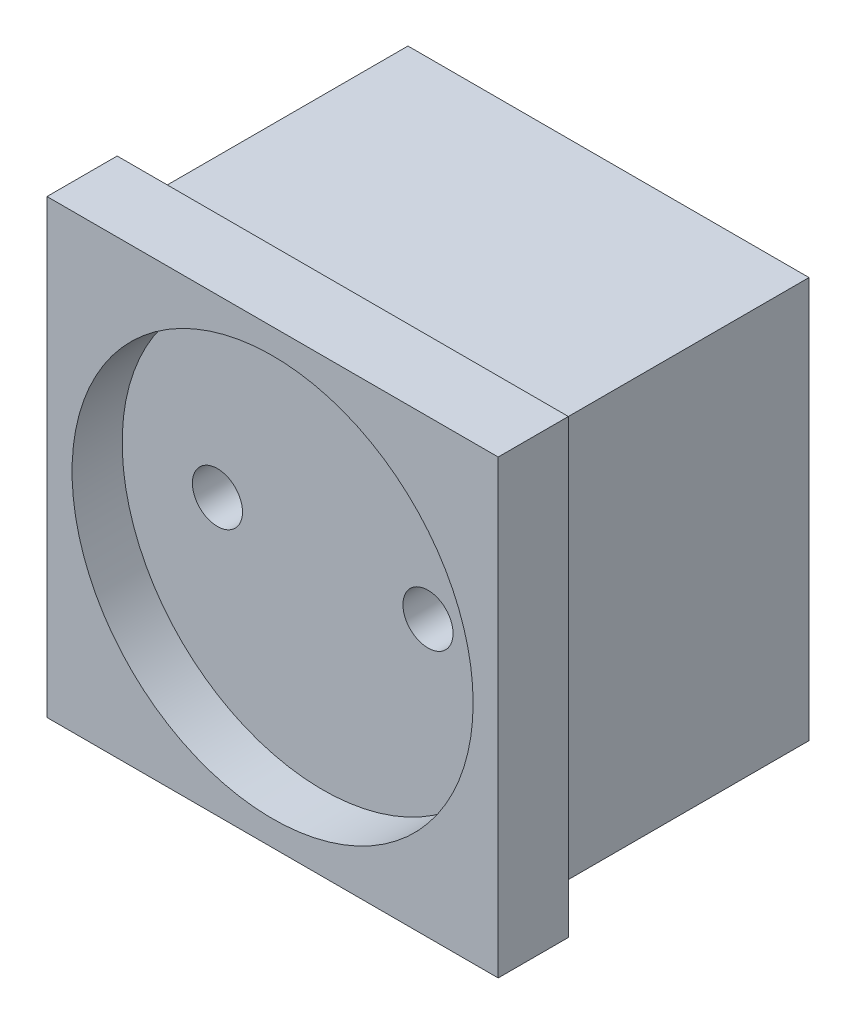
SolidWorks part; units mm, degrees
ref_plane "Спереди" through (0, 0, 0) normal (0, 0, 1) x (1, 0, 0)
ref_plane "Сверху" through (0, 0, 0) normal (0, 1, 0) x (1, 0, 0)
ref_plane "Справа" through (0, 0, 0) normal (1, 0, 0) x (0, 0, -1)
sketch "Эскиз1" plane through (0, 0, 0) normal (0, 0, 1) x (1, 0, 0)
  line L1 (-20, -20) -> (20, -20)
  line L2 (-20, -20) -> (-20, 20)
  line L3 (-20, 20) -> (20, 20)
  line L4 (20, -20) -> (20, 20)
  line L5 (-20, -20) -> (20, 20) construction
  line L6 (-20, 20) -> (20, -20) construction
  point P0 (0, 0)
  dimension "D1" = 40
extrude "Бобышка-Вытянуть1" add sketch "Эскиз1" along normal blind 33.5
sketch "Эскиз2" plane through (0, 0, 33.5) normal (0, 0, 1) x (1, 0, 0)
  line L1 (22.5, -22.5) -> (-22.5, -22.5)
  line L2 (22.5, -22.5) -> (22.5, 22.5)
  line L3 (22.5, 22.5) -> (-22.5, 22.5)
  line L4 (-22.5, -22.5) -> (-22.5, 22.5)
  line L5 (22.5, -22.5) -> (-22.5, 22.5) construction
  line L6 (22.5, 22.5) -> (-22.5, -22.5) construction
  point P0 (0, 0)
  dimension "D1" = 45
extrude "Бобышка-Вытянуть2" add sketch "Эскиз2" against normal blind 7
sketch "Эскиз3" plane through (0, 0, 33.5) normal (0, 0, 1) x (1, 0, 0)
  circle A0 centre (0, 0) radius 20
  dimension "D1" = 40
extrude "Вырез-Вытянуть3" cut sketch "Эскиз3" against normal blind 5
sketch "Эскиз4" plane through (0, 0, 28.5) normal (0, 0, 1) x (1, 0, 0)
  line L0 (0, 0) -> (0, 20) construction
  circle A0 centre (-10.5, 0) radius 2.5
  circle A1 centre (0, 0) radius 20 construction
  circle A2 centre (0, 0) radius 20 construction
  circle A3 centre (10.5, 0) radius 2.5
  point P9 (0, 0)
  dimension "D1" = 5
  dimension "D2" = 10.5
extrude "Вырез-Вытянуть4" cut sketch "Эскиз4" against normal blind 15 contours A0
